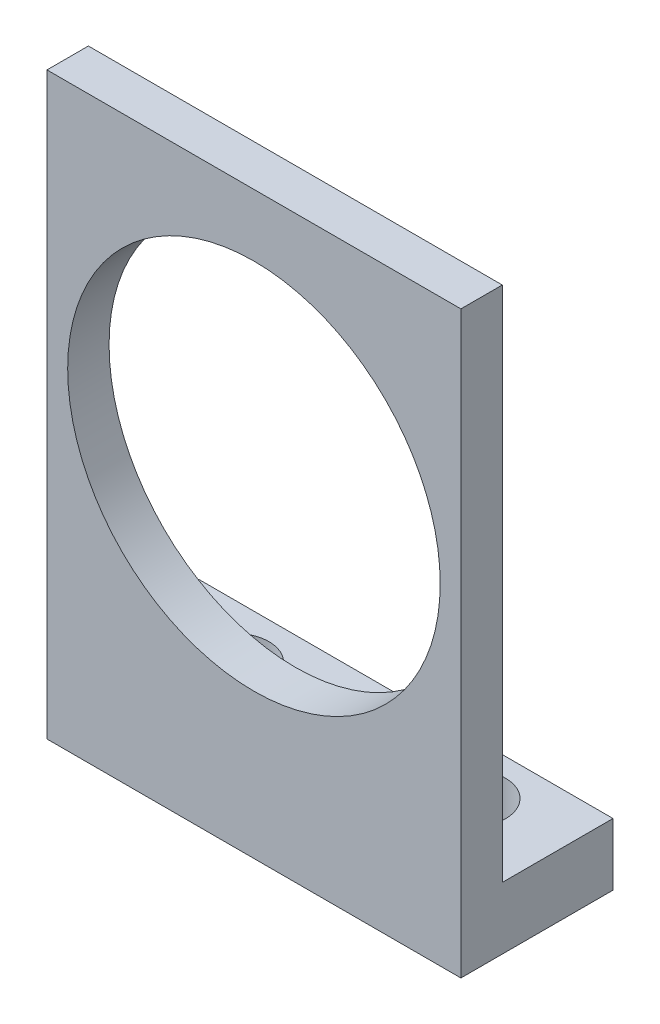
SolidWorks part; units mm, degrees
ref_plane "Front Plane" through (0, 0, 0) normal (0, 0, 1) x (1, 0, 0)
ref_plane "Top Plane" through (0, 0, 0) normal (0, 1, 0) x (1, 0, 0)
ref_plane "Right Plane" through (0, 0, 0) normal (1, 0, 0) x (0, 0, -1)
sketch "Sketch1" plane through (0, 0, 0) normal (0, 0, 1) x (1, 0, 0)
  line L1 (-10, -12.5) -> (10, -12.5)
  line L2 (-10, -12.5) -> (-10, 12.5)
  line L3 (-10, 12.5) -> (10, 12.5)
  line L4 (10, -12.5) -> (10, 12.5)
  line L5 (-10, -12.5) -> (10, 12.5) construction
  line L6 (-10, 12.5) -> (10, -12.5) construction
  point P0 (0, 0)
  dimension "D1" = 20
  dimension "D2" = 25
extrude "Boss-Extrude1" add sketch "Sketch1" along normal blind 2
sketch "Sketch2" plane through (0, -12.5, 0) normal (0, -1, 0) x (1, 0, 0)
  line L0 (-10, 2) -> (-10, 0) construction
  line L1 (-10, -5.35) -> (10, -5.35)
  line L2 (-10, -5.35) -> (-10, 7.35)
  line L3 (-10, 7.35) -> (10, 7.35)
  line L4 (10, -5.35) -> (10, 7.35)
  line L5 (-10, -5.35) -> (10, 7.35) construction
  line L6 (-10, 7.35) -> (10, -5.35) construction
  point P0 (0, 1)
  point P5 (0, 0)
  point P8 (-10, 1)
  dimension "D1" = 20
  dimension "D2" = 12.7
extrude "Boss-Extrude2" add sketch "Sketch2" along normal blind 3
sketch "Sketch3" plane through (0, -12.5, 0) normal (0, 1, 0) x (1, 0, 0)
sketch "Sketch5" plane through (0, -12.5, 0) normal (0, 1, 0) x (1, 0, 0)
sketch "Sketch6" plane through (0, -12.5, 0) normal (0, 1, 0) x (1, 0, 0)
  line L0 (-5.715, 2.7395) -> (5.715, 2.7395) construction
  point P0 (-5.715, 2.7395)
  point P3 (5.715, 2.7395)
  point P11 (0, 2.7395)
  point P12 (5.715, 2.7395)
  dimension "D1" = 11.43
hole_wizard "M3 Clearance Hole1" positions "Sketch6" profile "Sketch4" hole size "M3" standard "ANSI Metric" end condition up to next
sketch "Sketch4" plane through (-5.715, -12.5, -2.7395) normal (1, 0, 0) x (0, 0, 1)
  line L0 (0, 0) -> (0, 3)
  line L1 (0, 3) -> (1.7, 3)
  line L2 (1.7, 3) -> (1.7, 0)
  line L5 (1.7, 0) -> (0, 0)
  line L11 (0, -6.35) -> (0, 107.95) construction
  dimension "Thru Hole Dia." = 3.4
  dimension "Thru Hole Depth" = 3
sketch "Sketch7" plane through (0, 0, 2) normal (0, 0, 1) x (1, 0, 0)
  line L0 (10, 12.5) -> (-10, 12.5) construction
  circle A0 centre (0, 0.5) radius 9
  dimension "D2" = 18
  dimension "D1" = 12
extrude "Cut-Extrude1" cut sketch "Sketch7" against normal through all
sketch "Sketch8" plane through (0, -12.5, 0) normal (0, 1, 0) x (1, 0, 0)
  line L1 (10, -7.35) -> (-10, -7.35)
  line L2 (10, -7.35) -> (10, -2)
  line L3 (10, -2) -> (-10, -2)
  line L4 (-10, -7.35) -> (-10, -2)
extrude "Cut-Extrude2" cut sketch "Sketch8" against normal through all
